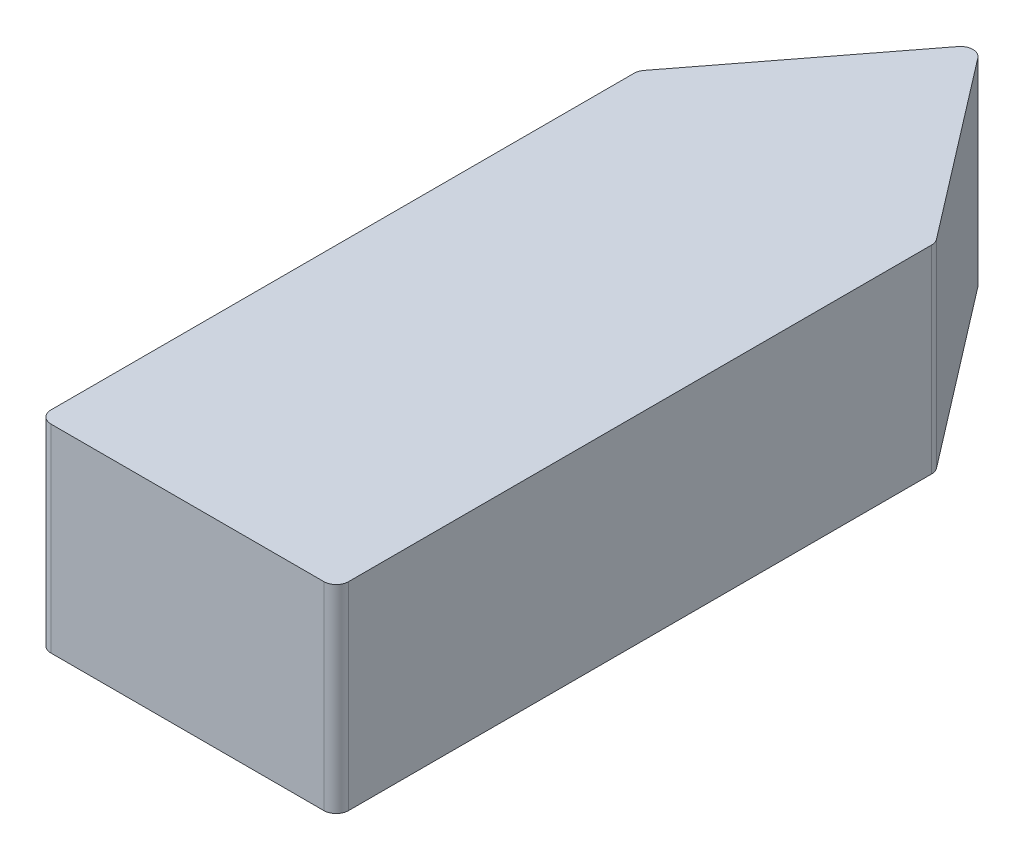
SolidWorks part; units mm, degrees
ref_plane "Front Plane" through (0, 0, 0) normal (0, 0, 1) x (1, 0, 0)
ref_plane "Top Plane" through (0, 0, 0) normal (0, 1, 0) x (1, 0, 0)
ref_plane "Right Plane" through (0, 0, 0) normal (1, 0, 0) x (0, 0, -1)
sketch "Sketch1" plane through (0, 0, 0) normal (0, 1, 0) x (1, 0, 0)
  line L0 (0, 0) -> (0, 101.6) construction
  line L1 (-17.4625, 0) -> (17.4625, 0)
  line L2 (19.05, 1.5875) -> (19.05, 76.2347)
  line L3 (-19.05, 1.5875) -> (-19.05, 76.2347)
  line L4 (18.7219, 77.2011) -> (1.2594, 99.9587)
  line L5 (-18.7219, 77.2011) -> (-1.2594, 99.9587)
  arc A0 (17.4625, 0) -> (19.05, 1.5875) centre (17.4625, 1.5875) ccw
  arc A1 (-19.05, 1.5875) -> (-17.4625, 0) centre (-17.4625, 1.5875) ccw
  arc A2 (1.2594, 99.9587) -> (-1.2594, 99.9587) centre (0, 98.9922) ccw
  arc A3 (-19.05, 76.2347) -> (-18.7219, 77.2011) centre (-17.4625, 76.2347) cw
  arc A4 (19.05, 76.2347) -> (18.7219, 77.2011) centre (17.4625, 76.2347) ccw
  point P9 (19.05, 0)
  point P12 (-19.05, 0)
  point P18 (-19.05, 76.7736)
  point P21 (19.05, 76.7736)
  dimension "D4" = 1.5875
  dimension "D1" = 38.1
  dimension "D2" = 101.6
  dimension "D3" = 75
extrude "Extrude1" add sketch "Sketch1" along normal blind 25.4
